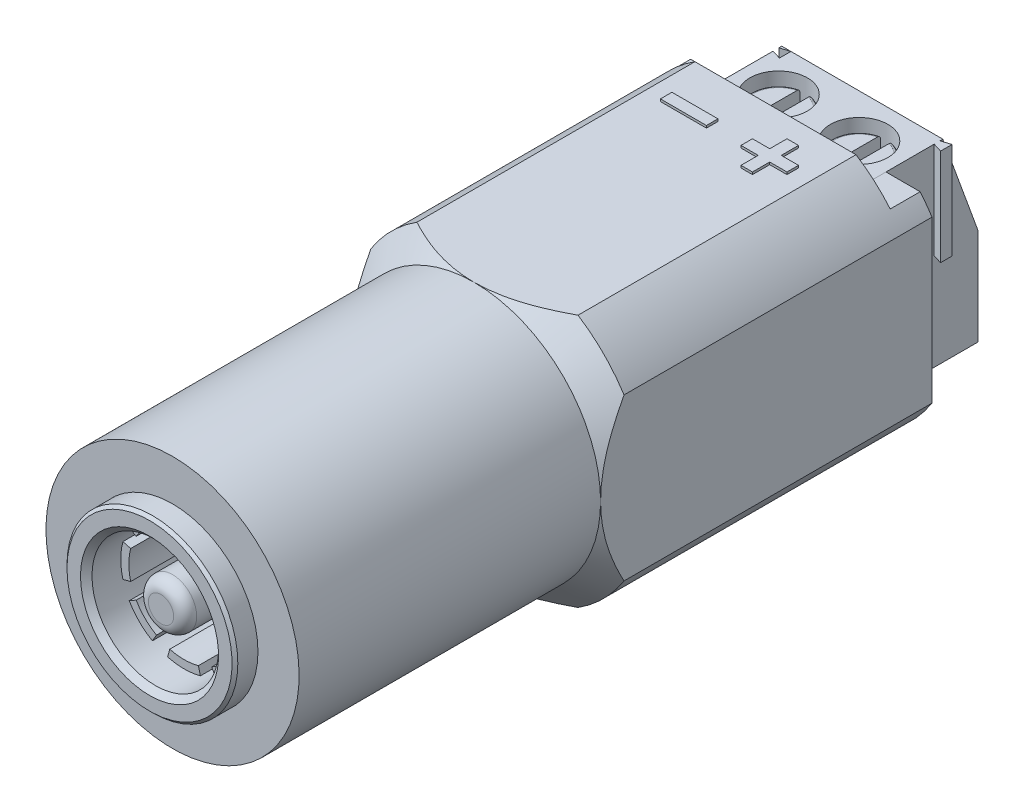
SolidWorks part; units mm, degrees
ref_plane "Front Plane" through (0, 0, 0) normal (0, 0, 1) x (1, 0, 0)
ref_plane "Top Plane" through (0, 0, 0) normal (0, 1, 0) x (1, 0, 0)
ref_plane "Right Plane" through (0, 0, 0) normal (1, 0, 0) x (0, 0, -1)
sketch "Sketch1" plane through (0, 0, 0) normal (1, 0, 0) x (0, 0, -1)
  line L0 (-16.25, 0) -> (16.25, 0) construction
  line L1 (-16.25, -2.75) -> (-16.25, 2.75) construction
  line L3 (-16.25, -1.05) -> (-16.25, 1.05) construction
  line L4 (0, -5.5) -> (0, 5.5) construction
  line L5 (16.25, 0) -> (14.7213, 4.2)
  line L6 (-15.25, -3.7125) -> (-15.25, 3.7125) construction
  line L7 (-16.25, 2.75) -> (-15.25, 2.75)
  line L8 (-15.25, 3.7125) -> (0, 3.7125) construction
  line L9 (-15.25, 2.75) -> (-15.25, 3.7125)
  line L10 (16.25, 0) -> (16.25, 4.2)
  line L11 (16.25, 4.2) -> (10.95, 4.2)
  line L12 (10.95, 4.2) -> (10.95, 5.5)
  line L13 (-15.25, 5.5) -> (10.95, 5.5)
  point P0 (-15.25, 0)
  point P4 (0, 0)
  point P9 (-16.25, 0)
  point P11 (-2.15, 5.5)
  point P12 (16.25, 0)
  point P15 (-16.25, 0)
  point P18 (0, 0)
  point P24 (-15.25, 0)
  point P28 (10.95, 0)
  point P35 (12.25, 4.2)
  dimension "Length" = 32.5
  dimension "For Plug End OD" = 5.5
  dimension "For Plug End ID" = 2.1
  dimension "OD" = 11
  dimension "D1" = 7.425
  dimension "Offset" = 5.3
  dimension "D3" = 8.4
  dimension "D4" = 20
  dimension "Body Length" = 27.5
  dimension "Body Offset" = 1
sketch "Sketch11" plane through (0, 0, 0) normal (0, 0, 1) x (1, 0, 0)
  line L0 (-3.5, 0) -> (3.5, 0)
  line L1 (-5.5, -5.5) -> (5.5, -5.5)
  line L2 (-5.5, -5.5) -> (-5.5, 5.5)
  line L3 (-5.5, 5.5) -> (5.5, 5.5)
  line L4 (5.5, -5.5) -> (5.5, 5.5)
  line L5 (0, 5.5) -> (0, -5.5) construction
  line L6 (-5.5, 0) -> (5.5, 0) construction
  point P0 (0, 0)
  point P7 (0, 0)
  dimension "D1" = 7
  dimension "Height" = 11
  dimension "Width" = 11
sketch "Sketch2" plane through (0, 0, 0) normal (1, 0, 0) x (0, 0, -1)
  line L0 (-15.25, 5.5) -> (10.95, 5.5)
  line L4 (10.95, 5.5) -> (10.95, 0)
  line L5 (-16.25, 0) -> (16.25, 0) construction
  line L6 (10.95, 0) -> (0, 0)
  line L11 (-15.25, 0) -> (0, 0)
  line L14 (-15.25, 5.5) -> (-15.25, 0)
revolve "Revolve1" add sketch "Sketch2" angle 360 about L6
sketch "Sketch12" plane through (0, 0, -10.95) normal (0, 0, -1) x (-1, 0, 0)
  line L0 (5.5, -5.5) -> (-5.5, -5.5) construction
  line L1 (5.5, -5.5) -> (5.5, 5.5) construction
  line L2 (-5.5, -5.5) -> (-5.5, 5.5) construction
  line L3 (5.5, 5.5) -> (-5.5, 5.5) construction
  line L4 (3.5, -5.5) -> (-3.5, -5.5)
  line L5 (5.5, -3.5) -> (5.5, 3.5)
  line L6 (-5.5, -3.5) -> (-5.5, 3.5)
  line L7 (3.5, 5.5) -> (-3.5, 5.5)
  line L12 (3.5, 0) -> (-3.5, 0) construction
  circle A0 centre (0, 0) radius 6.5192 construction
  arc A1 (-5.5, 3.5) -> (-3.5, 5.5) centre (0, 0) cw
  arc A2 (-5.5, -3.5) -> (-3.5, -5.5) centre (0, 0) ccw
  arc A3 (3.5, -5.5) -> (5.5, -3.5) centre (0, 0) ccw
  arc A4 (5.5, 3.5) -> (3.5, 5.5) centre (0, 0) ccw
extrude "Boss-Extrude3" add sketch "Sketch12" against normal up to vertex (13.1 mm away) up to point (0, 5.5, 2.15)
sketch "Sketch16" plane through (0, 0, 2.15) normal (0, 0, 1) x (1, 0, 0)
  line L0 (-3.5, 0) -> (3.5, 0) construction
  circle A0 centre (0, 0) radius 5.5
extrude "Cut-Extrude2" cut sketch "Sketch16" against normal through all draft 45 flip side to cut
sketch "Sketch15" plane through (0, 0, -10.95) normal (0, 0, -1) x (-1, 0, 0)
  line L0 (4.986, 4.2) -> (3.5, 4.2)
  line L1 (-3.5, 4.2) -> (-4.986, 4.2)
  line L2 (-3.5, 4.2) -> (-3.5, -4.2)
  line L3 (-3.5, -4.2) -> (3.5, -4.2)
  line L4 (3.5, -4.2) -> (3.5, 4.2)
  line L6 (0, -4.2) -> (0, 4.2) construction
  line L10 (-3.5, -5.5) -> (3.5, -5.5)
  line L12 (-5.5, 3.5) -> (-5.5, -3.5)
  line L14 (3.5, 5.5) -> (-3.5, 5.5)
  line L16 (5.5, -3.5) -> (5.5, 3.5)
  line L18 (-3.5, -5.5) -> (3.5, -5.5)
  line L20 (-5.5, 3.5) -> (-5.5, -3.5)
  line L24 (5.5, -3.5) -> (5.5, 3.5)
  arc A0 (5.5, 3.5) -> (3.5, 5.5) centre (0, 0) ccw construction
  arc A4 (-5.5, -3.5) -> (-3.5, -5.5) centre (0, 0) ccw
  arc A5 (-5.5, -3.5) -> (-3.5, -5.5) centre (0, 0) ccw
  arc A6 (-3.5, 5.5) -> (-5.5, 3.5) centre (0, 0) ccw
  arc A7 (-4.986, 4.2) -> (-5.5, 3.5) centre (0, 0) ccw
  arc A8 (5.5, 3.5) -> (3.5, 5.5) centre (0, 0) ccw
  arc A9 (5.5, 3.5) -> (4.986, 4.2) centre (0, 0) ccw
  arc A10 (3.5, -5.5) -> (5.5, -3.5) centre (0, 0) ccw
  arc A11 (3.5, -5.5) -> (5.5, -3.5) centre (0, 0) ccw
  point P0 (0, 4.2)
  point P5 (0, 4.2)
  point P25 (0, 0)
  dimension "D1" = 0
extrude "Boss-Extrude4" add sketch "Sketch15" along normal up to vertex (1.3 mm away) up to point (0, 4.2, -12.25)
sketch "Sketch17" plane through (0, 0, -10.95) normal (0, 0, -1) x (-1, 0, 0)
  line L1 (-3.5, 4.2) -> (3.5, 4.2)
  line L2 (-3.5, 4.2) -> (-3.5, -4.2)
  line L3 (-3.5, -4.2) -> (3.5, -4.2)
  line L4 (3.5, 4.2) -> (3.5, -4.2)
extrude "Boss-Extrude5" add sketch "Sketch17" along normal up to vertex (5.3 mm away) separate body up to point (0, 4.2, -16.25)
sketch "Sketch18" plane through (0, 0, 0) normal (1, 0, 0) x (0, 0, -1)
  line L0 (16.25, 0) -> (14.7213, 4.2) construction
  line L1 (16.25, 0) -> (14.7213, 4.2)
  line L2 (14.7213, 4.2) -> (16.25, 4.2)
  line L3 (16.25, 4.2) -> (16.25, 0)
extrude "Cut-Extrude3" cut sketch "Sketch18" against normal through all both and the other way through all
sketch "Sketch19" plane through (0, 4.2, 0) normal (0, 1, 0) x (1, 0, 0)
  line L0 (3.9, 14.2213) -> (3.5, 14.3463)
  line L1 (3.5, 14.7213) -> (3.9, 14.7213) construction
  line L2 (3.5, 14.7213) -> (3.5, 14.2213) construction
  line L3 (3.5, 14.2213) -> (3.9, 14.2213) construction
  line L4 (3.9, 14.7213) -> (3.9, 14.2213)
  line L5 (3.5, 14.3463) -> (3.5, 14.4713)
  line L6 (3.5, 14.4713) -> (3.5, 14.5963)
  line L7 (3.5, 14.5963) -> (3.9, 14.7213)
  dimension "D1" = 0.5
  dimension "D2" = 0.4
  dimension "D3" = 0.25
extrude "Boss-Extrude6" add sketch "Sketch19" against normal up to vertex (4.2 mm away) up to point (0, 0, -16.25)
sketch "Sketch21" plane through (0, 0, 0) normal (0, -1, 0) x (1, 0, 0)
  line L7 (0, 16.25) -> (0, -16.25) construction
  line L8 (0, 16.25) -> (0, -16.25) construction
  line L9 (-3.9, -14.7213) -> (-3.9, -14.2213) construction
  line L10 (-3.5, -14.5963) -> (-3.9, -14.7213) construction
  line L11 (-3.5, -14.4713) -> (-3.5, -14.5963) construction
  line L12 (3.9, -14.2213) -> (3.5, -14.3463)
  line L13 (3.5, -14.3463) -> (3.5, -14.4713)
  line L14 (3.5, -14.4713) -> (3.5, -14.5963)
  line L15 (3.5, -14.5963) -> (3.9, -14.7213)
  line L16 (3.9, -14.7213) -> (3.9, -14.2213)
  line L17 (3.9, -14.2213) -> (3.5, -14.3463) construction
  line L18 (3.5, -14.3463) -> (3.5, -14.4713) construction
  line L19 (3.5, -14.4713) -> (3.5, -14.5963) construction
  line L20 (3.5, -14.5963) -> (3.9, -14.7213) construction
  line L21 (3.9, -14.7213) -> (3.9, -14.2213) construction
  line L22 (-3.5, -14.3463) -> (-3.5, -14.4713) construction
  line L23 (-3.9, -14.2213) -> (-3.5, -14.3463) construction
  line L24 (-3.1, -14.2213) -> (-3.5, -14.3463)
  line L25 (-3.5, -14.5963) -> (-3.1, -14.7213)
  line L26 (-3.1, -14.7213) -> (-3.1, -14.2213)
  line L27 (-3.5, -14.3463) -> (-3.5, -14.5963)
  dimension "D1" = 0
extrude "Cut-Extrude4" cut sketch "Sketch21" against normal through all
sketch "Sketch22" plane through (0, 0, -16.25) normal (0, 0, -1) x (-1, 0, 0)
  line L0 (3.5, 0) -> (-3.5, 0) construction
  line L1 (-2.75, 0) -> (-0.375, 0)
  line L2 (-2.75, 0) -> (-2.75, -3.45)
  line L3 (-2.75, -3.45) -> (-0.375, -3.45)
  line L4 (-0.375, 0) -> (-0.375, -3.45)
  line L5 (-3.5, 0) -> (-2.75, 0) construction
  line L6 (0.375, 0) -> (2.75, 0)
  line L7 (0.375, 0) -> (0.375, -3.45)
  line L8 (0.375, -3.45) -> (2.75, -3.45)
  line L9 (2.75, 0) -> (2.75, -3.45)
  line L10 (-0.375, 0) -> (0.375, 0) construction
  line L11 (2.75, 0) -> (3.5, 0) construction
  line L12 (-1.5625, -3.45) -> (-1.5625, -4.2) construction
  line L13 (-3.5, -4.2) -> (3.5, -4.2) construction
  dimension "D1" = 0.75
extrude "Cut-Extrude5" cut sketch "Sketch22" against normal up to vertex (5.3 mm away) up to point (0, 4.2, -10.95)
sketch "Sketch23" plane through (0, 4.2, 0) normal (0, 1, 0) x (1, 0, 0)
  line L0 (0, 10.95) -> (0, 14.7213) construction
  line L1 (-1.75, 12.8357) -> (1.75, 12.8357) construction
  line L2 (-3, 12.8357) -> (-3.5, 12.8357) construction
  line L3 (-3.5, 14.3463) -> (-3.5, 10.95) construction
  circle A0 centre (-1.75, 12.8357) radius 1.25
  circle A1 centre (1.75, 12.8357) radius 1.25
  point P0 (0, 10.95)
  point P2 (0, 14.7213)
  point P9 (0, 12.8357)
  dimension "D1" = 0.5
  dimension "D2" = 2.5
extrude "Cut-Extrude6" cut sketch "Sketch23" against normal up to surface (7.65 mm away) up to face at (1.5625, -3.45, -13.6)
sketch "Sketch30" plane through (0, 0, 15.25) normal (0, 0, 1) x (1, 0, 0)
  circle A0 centre (0, 0) radius 3.7125
  point P0 (0, 3.7125)
extrude "Cut-Extrude8" cut sketch "Sketch30" against normal blind 4
sketch "Sketch6" plane through (0, 0, 0) normal (1, 0, 0) x (0, 0, -1)
  line L1 (-16.25, 2.75) -> (-11.25, 2.75)
  line L2 (-16.25, 2.75) -> (-16.25, 3.7125)
  line L3 (-16.25, 3.7125) -> (-11.25, 3.7125)
  line L4 (-11.25, 2.75) -> (-11.25, 3.7125)
  line L8 (-15.25, 3.7125) -> (0, 3.7125) construction
  line L9 (-15.25, -3.7125) -> (-15.25, 3.7125) construction
  dimension "D1" = 4
revolve "Revolve4" add sketch "Sketch6" angle 360 about L0
chamfer "Chamfer5" distance 0.25 angle 45 1 edges at (2.75, 0, 16.25)
chamfer "Chamfer6" distance 0.125 angle 45 1 edges at (3.7125, 0, 16.25)
sketch "Sketch25" plane through (0, 0, 0) normal (0, -1, 0) x (1, 0, 0)
  line L0 (0, 16.25) -> (0, -16.25) construction
  line L1 (0, 16.25) -> (0, -16.25) construction
  circle A1 centre (1.75, -12.8357) radius 1.2
  circle A2 centre (-1.75, -12.8357) radius 1.2
  circle A3 centre (-1.75, -12.8357) radius 1.2
  dimension "D1" = 0.05
extrude "Boss-Extrude7" add sketch "Sketch25" against normal offset from surface (3.7 mm away) 0.5 separate body up to face at (-1.75, 4.2, -11.5857)
sketch "Sketch26" plane through (0, 3.7, 0) normal (0, 1, 0) x (1, 0, 0)
  line L0 (-2.75, 16.25) -> (-0.375, 16.25) construction
  line L1 (1.5, 9.4213) -> (2, 9.4213)
  line L2 (1.5, 9.4213) -> (1.5, 16.25)
  line L3 (1.5, 16.25) -> (2, 16.25)
  line L4 (2, 9.4213) -> (2, 16.25)
  line L5 (1.75, 16.25) -> (1.75, 9.4213) construction
  line L6 (1.5, 12.8357) -> (2, 12.8357) construction
  line L7 (-2, 9.4213) -> (-1.5, 9.4213)
  line L8 (-2, 9.4213) -> (-2, 16.25)
  line L9 (-2, 16.25) -> (-1.5, 16.25)
  line L10 (-1.5, 9.4213) -> (-1.5, 16.25)
  line L11 (-1.75, 16.25) -> (-1.75, 9.4213) construction
  line L12 (-2, 12.8357) -> (-1.5, 12.8357) construction
  point P0 (1.75, 12.8357)
  point P4 (-1.75, 12.8357)
  dimension "D1" = 0.5
extrude "Cut-Extrude7" cut sketch "Sketch26" against normal blind 1
fillet "Fillet12" radius 0.125 2 edges at (-0.55, 3.7, -12.8357) (-2.95, 3.7, -12.8357)
fillet "Fillet13" radius 0.125 2 edges at (2.95, 3.7, -12.8357) (0.55, 3.7, -12.8357)
sketch "Sketch27" plane through (0, 0, -10.95) normal (0, 0, -1) x (-1, 0, 0)
  line L0 (-2.45, -3.25) -> (-0.675, -3.25)
  line L1 (-1.5625, -3.45) -> (-1.5625, -4.2) construction
  line L2 (-0.375, 0) -> (-0.375, -3.45) construction
  line L3 (-2.75, -3.45) -> (-0.375, -3.45) construction
  line L4 (-2.65, -3.05) -> (-2.65, -0.125)
  line L6 (-2.65, -0.125) -> (-2.0625, -0.125)
  line L7 (-2.0625, -0.125) -> (-2.0625, -1.1017)
  line L8 (-2.4625, -1.85) -> (-2.65, -1.85) construction
  line L9 (-1.5625, -3.25) -> (-1.5625, -2.75) construction
  line L10 (0, -1.05) -> (0, 1.05) construction
  line L11 (0, -1.05) -> (0, 1.05) construction
  line L12 (3.5, 0) -> (-3.5, 0) construction
  line L13 (-0.475, -3.05) -> (-0.475, -0.125)
  line L14 (-0.475, -0.125) -> (-1.0625, -0.125)
  line L15 (-1.0625, -0.125) -> (-1.0625, -1.1017)
  line L16 (1.5625, -3.25) -> (1.5625, -2.75) construction
  line L17 (2.4625, -1.85) -> (2.65, -1.85) construction
  line L18 (1.0625, -0.125) -> (1.0625, -1.1017)
  line L19 (0.475, -0.125) -> (1.0625, -0.125)
  line L20 (0.475, -3.05) -> (0.475, -0.125)
  line L21 (2.0625, -0.125) -> (2.0625, -1.1017)
  line L22 (2.65, -0.125) -> (2.0625, -0.125)
  line L23 (2.65, -3.05) -> (2.65, -0.125)
  line L24 (2.45, -3.25) -> (0.675, -3.25)
  arc A0 (-2.0625, -1.1017) -> (-1.0625, -1.1017) centre (-1.5625, -1.85) ccw
  arc A1 (2.0625, -1.1017) -> (1.0625, -1.1017) centre (1.5625, -1.85) cw
  arc A2 (2.65, -3.05) -> (2.45, -3.25) centre (2.45, -3.05) cw
  arc A3 (0.475, -3.05) -> (0.675, -3.25) centre (0.675, -3.05) ccw
  arc A4 (-0.675, -3.25) -> (-0.475, -3.05) centre (-0.675, -3.05) ccw
  arc A5 (-2.45, -3.25) -> (-2.65, -3.05) centre (-2.45, -3.05) cw
  point P3 (-1.5625, -3.25)
  point P40 (2.65, -3.25)
  point P43 (0.475, -3.25)
  point P46 (-0.475, -3.25)
  point P49 (-2.65, -3.25)
  dimension "D3" = 0.9
  dimension "D7" = 0.2
  dimension "D1" = 0.1
  dimension "D2" = 0.2
  dimension "D4" = 0.125
  dimension "D5" = 0.5
  dimension "D6" = 1
extrude "Boss-Extrude8" add sketch "Sketch27" along normal up to vertex (5.3 mm away) separate body up to point (2.75, -3.45, -16.25)
sketch "Sketch28" plane through (0, 0, -16.25) normal (0, 0, -1) x (-1, 0, 0)
  line L0 (-1.0625, -0.125) -> (-1.0625, -1.1017) construction
  line L1 (-2.0625, -1.1017) -> (-1.0625, -1.1017)
  line L2 (-2.0625, -1.1017) -> (-2.0625, -0.6133)
  line L3 (-2.0625, -0.6133) -> (-1.0625, -0.6133)
  line L4 (-1.0625, -1.1017) -> (-1.0625, -0.6133)
  line L5 (0, -3.7125) -> (0, 3.7125) construction
  line L6 (0, -3.7125) -> (0, 3.7125) construction
  line L7 (1.0625, -1.1017) -> (1.0625, -0.6133)
  line L8 (2.0625, -0.6133) -> (1.0625, -0.6133)
  line L9 (2.0625, -1.1017) -> (2.0625, -0.6133)
  line L10 (2.0625, -1.1017) -> (1.0625, -1.1017)
extrude "Boss-Extrude9" add sketch "Sketch28" against normal blind 2 separate body
fillet "Fillet14" radius 0.2 2 edges at (1.5625, -1.1017, -16.25) (1.5625, -0.6133, -16.25)
fillet "Fillet15" radius 0.2 2 edges at (-1.5625, -1.1017, -16.25) (-1.5625, -0.6133, -16.25)
sketch "Sketch31" plane through (0, 0, 11.25) normal (0, 0, 1) x (1, 0, 0)
  circle A0 centre (0, 0) radius 1.05
  point P0 (0, 1.05)
extrude "Boss-Extrude11" add sketch "Sketch31" along normal offset from surface (4.5 mm away) 0.5 separate body up to face at (-3.5875, 0, 16.25)
sketch "Sketch32" plane through (0, 0, 15.75) normal (0, 0, 1) x (1, 0, 0)
  line L0 (0, 0) -> (-0.7118, 2.6563) construction
  line L1 (0, 0) -> (0.7118, 2.6563) construction
  line L2 (-0.6212, 2.3182) -> (-0.7118, 2.6563)
  line L3 (0.6212, 2.3182) -> (0.7118, 2.6563)
  line L4 (2.0785, 1.2) -> (2.3816, 1.375)
  line L5 (1.2, 2.0785) -> (1.375, 2.3816)
  line L6 (2.3182, -0.6212) -> (2.6563, -0.7118)
  line L7 (2.3182, 0.6212) -> (2.6563, 0.7118)
  line L8 (1.2, -2.0785) -> (1.375, -2.3816)
  line L9 (2.0785, -1.2) -> (2.3816, -1.375)
  line L10 (-0.6212, -2.3182) -> (-0.7118, -2.6563)
  line L11 (0.6212, -2.3182) -> (0.7118, -2.6563)
  line L12 (-2.0785, -1.2) -> (-2.3816, -1.375)
  line L13 (-1.2, -2.0785) -> (-1.375, -2.3816)
  line L14 (-2.3182, 0.6212) -> (-2.6563, 0.7118)
  line L15 (-2.3182, -0.6212) -> (-2.6563, -0.7118)
  line L16 (-1.2, 2.0785) -> (-1.375, 2.3816)
  line L17 (-2.0785, 1.2) -> (-2.3816, 1.375)
  circle A0 centre (0, 0) radius 2.75 construction
  arc A1 (-0.7118, 2.6563) -> (0.7118, 2.6563) centre (0, 0) cw
  arc A2 (-0.6212, 2.3182) -> (0.6212, 2.3182) centre (0, 0) cw
  arc A3 (1.2, 2.0785) -> (2.0785, 1.2) centre (0, 0) cw
  arc A4 (1.375, 2.3816) -> (2.3816, 1.375) centre (0, 0) cw
  arc A5 (2.3182, 0.6212) -> (2.3182, -0.6212) centre (0, 0) cw
  arc A6 (2.6563, 0.7118) -> (2.6563, -0.7118) centre (0, 0) cw
  arc A7 (2.0785, -1.2) -> (1.2, -2.0785) centre (0, 0) cw
  arc A8 (2.3816, -1.375) -> (1.375, -2.3816) centre (0, 0) cw
  arc A9 (0.6212, -2.3182) -> (-0.6212, -2.3182) centre (0, 0) cw
  arc A10 (0.7118, -2.6563) -> (-0.7118, -2.6563) centre (0, 0) cw
  arc A11 (-1.2, -2.0785) -> (-2.0785, -1.2) centre (0, 0) cw
  arc A12 (-1.375, -2.3816) -> (-2.3816, -1.375) centre (0, 0) cw
  arc A13 (-2.3182, -0.6212) -> (-2.3182, 0.6212) centre (0, 0) cw
  arc A14 (-2.6563, -0.7118) -> (-2.6563, 0.7118) centre (0, 0) cw
  arc A15 (-2.0785, 1.2) -> (-1.2, 2.0785) centre (0, 0) cw
  arc A16 (-2.3816, 1.375) -> (-1.375, 2.3816) centre (0, 0) cw
  point P0 (0, 2.75)
  point P41 (0, 0)
  dimension "D1" = 30
  dimension "D2" = 0.35
  dimension "D3" = 8
extrude "Boss-Extrude12" add sketch "Sketch32" against normal up to surface (3.5 mm away) from offset 1 up to face at (3.7125, 0, 11.25) offset against normal yes
fillet "Fillet17" radius 0.5 1 edges at (-1.05, 0, 15.75)
sketch "Sketch29" plane through (0, 5.5, 0) normal (0, 1, 0) x (1, 0, 0)
  line L0 (0, 0) -> (0, 14.7213) construction
  line L1 (-3.1, 14.7213) -> (3.5, 14.7213) construction
  line L2 (2.75, 8.95) -> (-2.75, 8.95) construction
  line L3 (-3.5, 10.95) -> (3.5, 10.95) construction
  line L4 (-3.5, -1.1308) -> (-3.5, 10.95) construction
  line L5 (2.75, 8.7) -> (2, 8.7)
  line L6 (-0.75, 9.2) -> (-2.75, 9.2)
  line L7 (-0.75, 9.2) -> (-0.75, 8.7)
  line L8 (-0.75, 8.7) -> (-2.75, 8.7)
  line L9 (-2.75, 9.2) -> (-2.75, 8.7)
  line L10 (-1.75, 8.7) -> (-1.75, 9.2) construction
  line L11 (-0.75, 8.95) -> (-2.75, 8.95) construction
  line L12 (0.75, 9.2) -> (2.75, 9.2) construction
  line L13 (0.75, 9.2) -> (0.75, 8.7) construction
  line L14 (0.75, 8.7) -> (2.75, 8.7) construction
  line L15 (2.75, 9.2) -> (2.75, 8.7) construction
  line L16 (1.75, 8.7) -> (1.75, 9.2) construction
  line L17 (0.75, 8.95) -> (2.75, 8.95) construction
  line L18 (2, 9.95) -> (1.5, 9.95) construction
  line L19 (2, 9.95) -> (2, 7.95) construction
  line L20 (2, 7.95) -> (1.5, 7.95) construction
  line L21 (1.5, 9.95) -> (1.5, 7.95) construction
  line L22 (1.75, 7.95) -> (1.75, 9.95) construction
  line L23 (2, 8.95) -> (1.5, 8.95) construction
  line L24 (2, 8.7) -> (2, 7.95)
  line L25 (2, 7.95) -> (1.5, 7.95)
  line L26 (1.5, 7.95) -> (1.5, 8.7)
  line L27 (1.5, 8.7) -> (0.75, 8.7)
  line L28 (0.75, 8.7) -> (0.75, 9.2)
  line L29 (0.75, 9.2) -> (1.5, 9.2)
  line L30 (1.5, 9.2) -> (1.5, 9.95)
  line L31 (1.5, 9.95) -> (2, 9.95)
  line L32 (2, 9.95) -> (2, 9.2)
  line L33 (2, 9.2) -> (2.75, 9.2)
  line L34 (2.75, 9.2) -> (2.75, 8.7)
  point P8 (0, 8.95)
  point P12 (-1.75, 8.95)
  point P17 (1.75, 8.95)
  point P21 (1.75, 8.95)
  dimension "D1" = 2
  dimension "D2" = 0.75
  dimension "D3" = 2
  dimension "D4" = 0.5
extrude "Boss-Extrude10" add sketch "Sketch29" along normal blind 0.1
equation "\"D1@Sketch1\"=\"For Plug End OD@Sketch1\" * 1.35"
